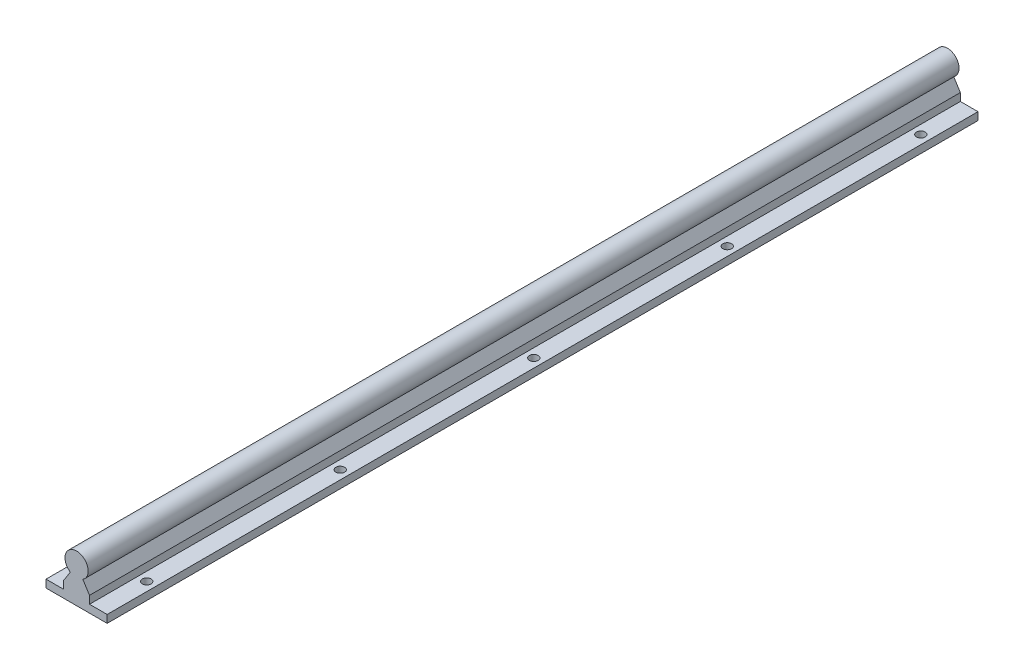
SolidWorks part; units mm, degrees
ref_plane "Front Plane" through (0, 0, 0) normal (0, 0, 1) x (1, 0, 0)
ref_plane "Top Plane" through (0, 0, 0) normal (0, 1, 0) x (1, 0, 0)
ref_plane "Right Plane" through (0, 0, 0) normal (1, 0, 0) x (0, 0, -1)
sketch "Sketch1" plane through (0, 0, 0) normal (0, 0, 1) x (1, 0, 0)
  line L0 (-15.8, 0) -> (15.8, 0)
  line L1 (0, 34.0275) -> (0, -13.4099) construction
  line L2 (-15.8, 0) -> (-15.8, 4)
  line L3 (-15.8, 4) -> (-6.6892, 4)
  line L4 (-6.6892, 4) -> (-6.6892, 8)
  line L5 (15.8, 0) -> (15.8, 4)
  line L6 (-6.6892, 8) -> (-3.2238, 13.4397)
  line L7 (15.8, 4) -> (6.6892, 4)
  line L8 (6.6892, 8) -> (3.2238, 13.4397)
  line L9 (6.6892, 4) -> (6.6892, 8)
  arc A0 (3.2238, 13.4397) -> (-3.2238, 13.4397) centre (0, 18.5) ccw
  dimension "D1" = 12
  dimension "D2" = 18.5
  dimension "D3" = 31.6
  dimension "D4" = 4
  dimension "D5" = 32.5
  dimension "D7" = 8
extrude "Boss-Extrude1" add sketch "Sketch1" along normal blind 450
sketch "Sketch3" plane through (0, 0, 0) normal (0, 1, 0) x (1, 0, 0)
  line L0 (0, 0) -> (0, -38.1671) construction
  line L1 (-6.6892, 0) -> (-15.8, 0) construction
  circle A0 centre (-11.2446, -25) radius 2.25
  circle A1 centre (11.2446, -25) radius 2.25
  circle A2 centre (-11.2446, -125) radius 2.25
  circle A3 centre (11.2446, -125) radius 2.25
  circle A4 centre (-11.2446, -225) radius 2.25
  circle A5 centre (11.2446, -225) radius 2.25
  circle A6 centre (-11.2446, -325) radius 2.25
  circle A7 centre (11.2446, -325) radius 2.25
  circle A8 centre (-11.2446, -425) radius 2.25
  circle A9 centre (11.2446, -425) radius 2.25
  point P7 (-11.2446, 0)
  dimension "D1" = 4.5
  dimension "D2" = 25
  dimension "D3" = 5
extrude "Cut-Extrude2" cut sketch "Sketch3" along normal through all
